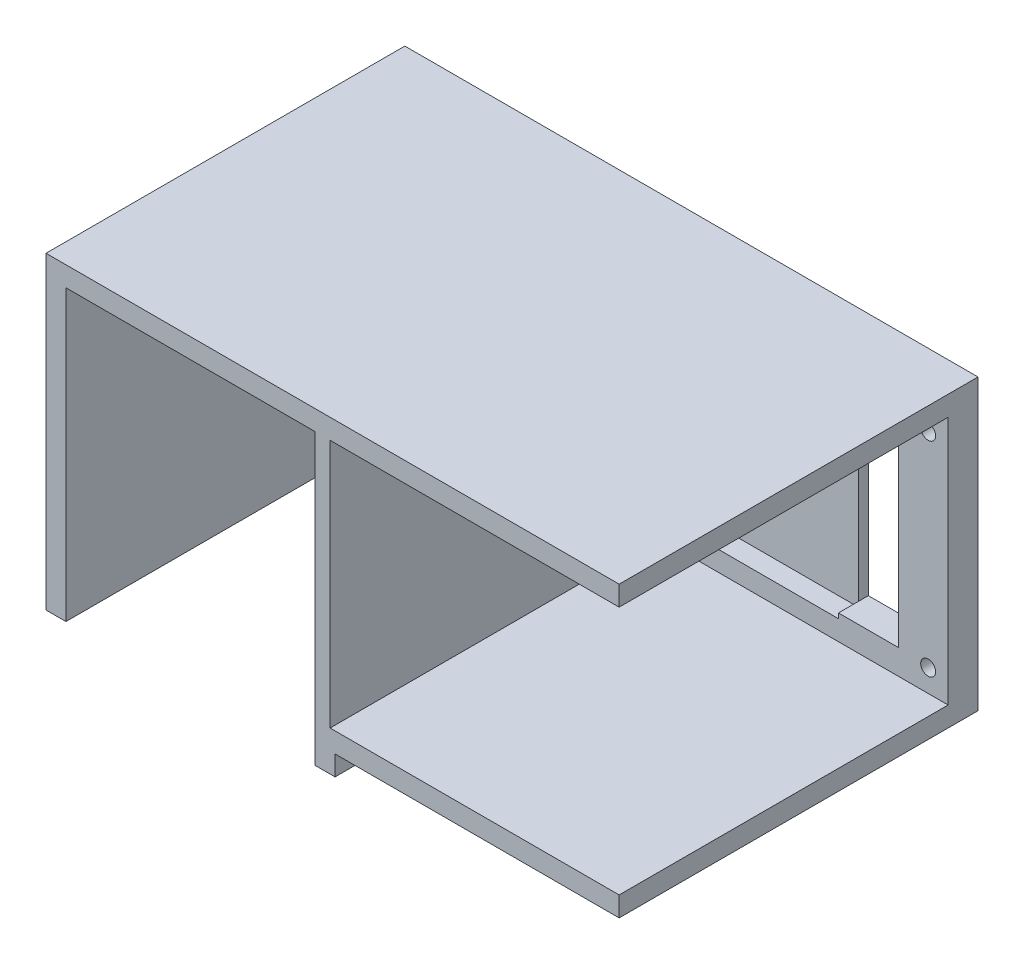
SolidWorks part; units mm, degrees
ref_plane "前视基准面" through (0, 0, 0) normal (0, 0, 1) x (1, 0, 0)
ref_plane "上视基准面" through (0, 0, 0) normal (0, 1, 0) x (1, 0, 0)
ref_plane "右视基准面" through (0, 0, 0) normal (1, 0, 0) x (0, 0, -1)
other "Configuration Table"
sketch "草图1" plane through (0, 0, 0) normal (0, 0, 1) x (1, 0, 0)
  line L0 (0, 0) -> (57.5, 0)
  line L1 (57.5, 0) -> (57.5, -29)
  line L2 (57.5, -29) -> (29, -29)
  line L3 (29, -29) -> (29, -31)
  line L4 (29, -31) -> (0, -31)
  line L5 (0, -31) -> (0, 0)
  dimension "D1" = 29
  dimension "D2" = 31
  dimension "D3" = 57.5
  dimension "D4" = 29
extrude "凸台-拉伸1" add sketch "草图1" along normal blind 3
sketch "草图2" plane through (0, 0, 3) normal (0, 0, 1) x (1, 0, 0)
  line L0 (14.5, -50) -> (14.5, -50050) construction
  line L1 (0, -31) -> (29, -31) construction
  line L2 (71, -14.5) -> (-49929, -14.5) construction
  line L3 (57.5, -29) -> (57.5, 0) construction
  line L5 (4.25, -29) -> (24.75, -29) construction
  line L6 (4.25, -29) -> (4.25, -4.55) construction
  line L7 (4.25, -4.55) -> (24.75, -4.55) construction
  line L8 (24.75, -29) -> (24.75, -4.55) construction
  line L9 (55.5, -24.75) -> (31.05, -24.75) construction
  line L10 (55.5, -24.75) -> (55.5, -4.25) construction
  line L11 (55.5, -4.25) -> (31.05, -4.25) construction
  line L12 (31.05, -24.75) -> (31.05, -4.25) construction
  circle A0 centre (31.05, -4.25) radius 0.75
  circle A1 centre (55.5, -4.25) radius 0.75
  circle A2 centre (31.05, -24.75) radius 0.75
  circle A3 centre (55.5, -24.75) radius 0.75
  circle A4 centre (4.25, -29) radius 0.75
  circle A5 centre (24.75, -29) radius 0.75
  circle A6 centre (4.25, -4.55) radius 0.75
  circle A7 centre (24.75, -4.55) radius 0.75
  point P4 (14.5, -31)
  point P9 (57.5, -14.5)
  point P14 (14.5, -29)
  point P27 (55.5, -14.5)
  dimension "D7" = 1.5
  dimension "D8" = 1.5
  dimension "D9" = 1.5
  dimension "D10" = 1.5
  dimension "D11" = 1.5
  dimension "D12" = 1.5
  dimension "D13" = 1.5
  dimension "D14" = 1.5
  dimension "D1" = 24.45
  dimension "D2" = 20.5
  dimension "D3" = 2
  dimension "D4" = 20.5
  dimension "D5" = 24.45
  dimension "D6" = 2
extrude "切除-拉伸1" cut sketch "草图2" against normal up to next
sketch "草图3" plane through (0, -31, 0) normal (0, -1, 0) x (1, 0, 0)
  line L0 (14.5, 0) -> (14.5, -50000) construction
  line L1 (0, 0) -> (29, 0) construction
  line L2 (0, 3) -> (29, 3) construction
  line L3 (4, 3) -> (25, 3)
  line L4 (4, 3) -> (4, 1)
  line L5 (4, 1) -> (25, 1)
  line L6 (25, 3) -> (25, 1)
  point P4 (14.5, 0)
  point P9 (14.5, 3)
  dimension "D1" = 2
  dimension "D2" = 21
extrude "切除-拉伸2" [suppressed] cut sketch "草图3" against normal blind 24
sketch "草图4" plane through (0, 0, 0) normal (0, 0, -1) x (-1, 0, 0)
  line L1 (-14.5, -30) -> (-14.5, 49970) construction
  line L2 (0, -31) -> (-29, -31) construction
  line L4 (-24.5, -26) -> (-4.5, -26)
  line L5 (-24.5, -26) -> (-24.5, -20)
  line L6 (-24.5, -20) -> (-4.5, -20)
  line L7 (-4.5, -26) -> (-4.5, -20)
  point P6 (-14.5, -31)
  point P9 (-14.5, -20)
  dimension "D1" = 20
  dimension "D2" = 6
  dimension "D3" = 5
extrude "切除-拉伸3" cut sketch "草图4" against normal up to next
sketch "草图5" plane through (0, 0, 0) normal (0, 0, -1) x (-1, 0, 0)
  line L0 (-56, -14.5) -> (49944, -14.5) construction
  line L1 (-57.5, -29) -> (-57.5, 0) construction
  line L3 (-52.5, -4.5) -> (-46.5, -4.5)
  line L4 (-52.5, -4.5) -> (-52.5, -24.5)
  line L5 (-52.5, -24.5) -> (-46.5, -24.5)
  line L6 (-46.5, -4.5) -> (-46.5, -24.5)
  point P4 (-57.5, -14.5)
  point P9 (-52.5, -14.5)
  dimension "D1" = 20
  dimension "D2" = 6
  dimension "D3" = 5
extrude "切除-拉伸4" cut sketch "草图5" against normal up to next
sketch "草图7" plane through (0, -20, 0) normal (0, -1, 0) x (1, 0, 0)
  line L0 (14.5, 0) -> (14.5, -50000) construction
  line L1 (0, 0) -> (29, 0) construction
  line L2 (0, 3) -> (29, 3) construction
  line L3 (4, 3) -> (25, 3)
  line L4 (4, 3) -> (4, 1)
  line L5 (4, 1) -> (25, 1)
  line L6 (25, 3) -> (25, 1)
  point P4 (14.5, 0)
  point P9 (14.5, 3)
  dimension "D1" = 21
  dimension "D2" = 2
extrude "切除-拉伸6" cut sketch "草图7" against normal blind 13
sketch "草图8" plane through (46.5, 0, 0) normal (1, 0, 0) x (0, 0, -1)
  line L0 (0, -14.5) -> (50000, -14.5) construction
  line L1 (0, -29) -> (0, 0) construction
  line L2 (-3, -29) -> (-3, 0) construction
  line L3 (-3, -4) -> (-1, -4)
  line L4 (-3, -4) -> (-3, -25)
  line L5 (-3, -25) -> (-1, -25)
  line L6 (-1, -4) -> (-1, -25)
  point P4 (0, -14.5)
  point P9 (-1, -14.5)
  dimension "D1" = 21
  dimension "D2" = 2
extrude "切除-拉伸7" cut sketch "草图8" against normal blind 13
sketch "草图9" plane through (0, 0, 3) normal (0, 0, 1) x (1, 0, 0)
  line L0 (2, -31) -> (2, -2)
  line L1 (2, -2) -> (57.5, -2)
  line L2 (57.5, -27) -> (27, -27)
  line L3 (27, -27) -> (27, -31)
  line L4 (27, -27) -> (27, -2)
  line L5 (28.5, -27) -> (28.5, -2)
  line L6 (0, 0) -> (0, -31)
  line L7 (0, -31) -> (29, -31)
  line L8 (29, -31) -> (29, -29)
  line L9 (29, -29) -> (57.5, -29)
  line L10 (57.5, -29) -> (57.5, 0)
  line L11 (57.5, 0) -> (0, 0)
  line L12 (0, 0) -> (0, -31)
  line L13 (0, -31) -> (29, -31)
  line L14 (29, -31) -> (29, -29)
  line L15 (29, -29) -> (57.5, -29)
  line L16 (57.5, -29) -> (57.5, 0)
  line L17 (57.5, 0) -> (0, 0)
  line M37 (0, 0) -> (0, -31)
  line M38 (0, -31) -> (29, -31)
  line M39 (29, -31) -> (29, -29)
  line M40 (29, -29) -> (57.5, -29)
  line M41 (57.5, -29) -> (57.5, 0)
  line M42 (57.5, 0) -> (0, 0)
  dimension "D2" = 2
  dimension "D3" = 2
  dimension "D4" = 2
  dimension "D5" = 2
  dimension "D6" = 1.5
  dimension "D1" = 0
extrude "凸台-拉伸2" add sketch "草图9" along normal blind 33 contours L0 L1 M41 M42 M37 M38 | L2 L5 L1 L4 | L2 L3 M38 M39 M40 M41
